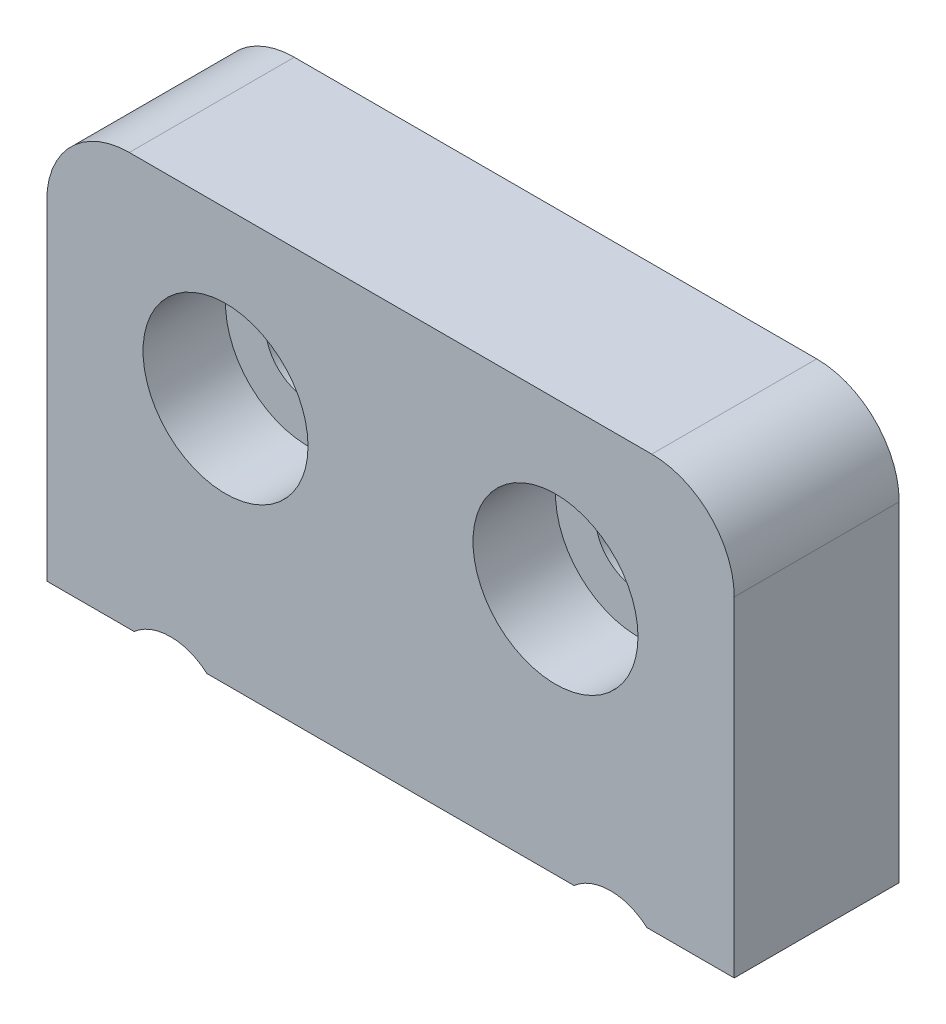
SolidWorks part; units mm, degrees
ref_plane "正面" through (0, 0, 0) normal (0, 0, 1) x (1, 0, 0)
ref_plane "平面" through (0, 0, 0) normal (0, 1, 0) x (1, 0, 0)
ref_plane "右側面" through (0, 0, 0) normal (1, 0, 0) x (0, 0, -1)
sketch "ｽｹｯﾁ1" plane through (0, 0, 0) normal (0, 0, 1) x (1, 0, 0)
  line L0 (12.5, 15) -> (12.5, 0) construction
  line L1 (0, 0) -> (25, 0)
  line L2 (0, 0) -> (0, 15)
  line L3 (0, 15) -> (25, 15)
  line L4 (25, 0) -> (25, 15)
  circle A0 centre (6.5, 9) radius 1.55
  circle A1 centre (18.5, 9) radius 1.55
  dimension "D2" = 12
  dimension "D3" = 3.1
  dimension "D4" = 9
  dimension "D1" = 25
  dimension "D5" = 15
extrude "ﾎﾞｽ - 押し出し1" add sketch "ｽｹｯﾁ1" along normal blind 6
sketch "ｽｹｯﾁ3" plane through (0, 0, 0) normal (0, -1, 0) x (1, 0, 0)
  line L0 (12.5, 6) -> (12.5, 0) construction
  line L1 (0, 6) -> (25, 6) construction
  line L2 (0, 0) -> (25, 0) construction
  line L3 (4.5, 3) -> (12.5, 3) construction
  circle A0 centre (4.5, 3) radius 1.5
  circle A1 centre (20.5, 3) radius 1.5
  dimension "D1" = 16
  dimension "D2" = 3
extrude "ｶｯﾄ - 押し出し1" cut sketch "ｽｹｯﾁ3" against normal blind 6
sketch "ｽｹｯﾁ4" plane through (0, 0, 6) normal (0, 0, 1) x (1, 0, 0)
  line L0 (12.5, 15) -> (12.5, 0) construction
  line L1 (25, 15) -> (0, 15) construction
  line L2 (0, 0) -> (25, 0) construction
  line L3 (4.5, -1.5) -> (4.5, 0) construction
  line L4 (3.1771, 0) -> (5.8229, 0)
  line L5 (21.8229, 0) -> (19.1771, 0)
  arc A0 (3.1771, 0) -> (5.8229, 0) centre (4.5, -1.5) cw
  arc A1 (21.8229, 0) -> (19.1771, 0) centre (20.5, -1.5) ccw
  dimension "D1" = 8
  dimension "D2" = 2
  dimension "D3" = 1.5
extrude "ｶｯﾄ - 押し出し2" cut sketch "ｽｹｯﾁ4" against normal through all
fillet "ﾌｨﾚｯﾄ1" radius 3 2 edges at (0, 15, 3) (25, 15, 3)
sketch "ｽｹｯﾁ5" plane through (0, 0, 6) normal (0, 0, 1) x (1, 0, 0)
  circle A0 centre (6.5, 9) radius 3
  circle A1 centre (18.5, 9) radius 3
  dimension "D1" = 6
extrude "ｶｯﾄ - 押し出し3" cut sketch "ｽｹｯﾁ5" against normal blind 3
